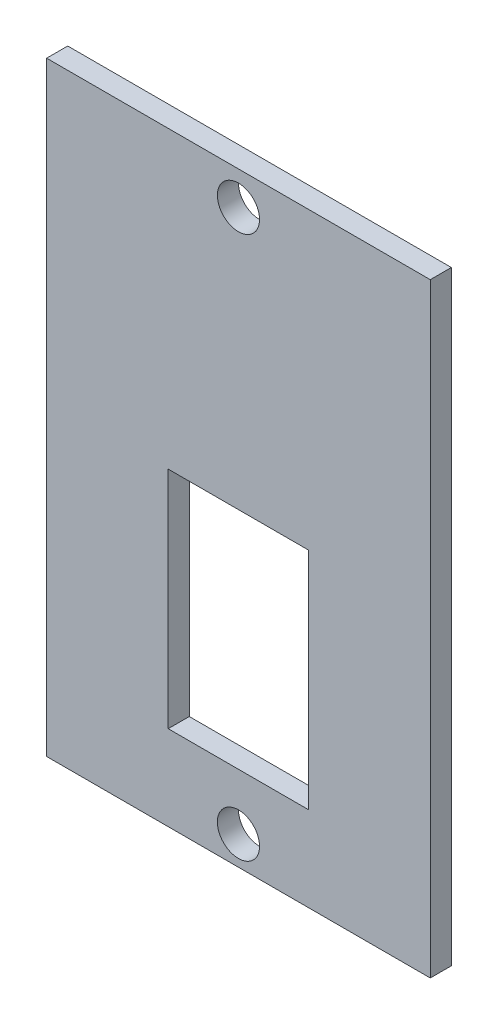
SolidWorks part; units mm, degrees
ref_plane "前视基准面" through (0, 0, 0) normal (0, 0, 1) x (1, 0, 0)
ref_plane "上视基准面" through (0, 0, 0) normal (0, 1, 0) x (1, 0, 0)
ref_plane "右视基准面" through (0, 0, 0) normal (1, 0, 0) x (0, 0, -1)
other "Configuration Table"
sketch "草图1" plane through (0, 0, 0) normal (0, 0, 1) x (1, 0, 0)
  line L0 (7.65, -10.5601) -> (-7.65, -10.5601) construction
  line L2 (-13.65, 14.6) -> (-13.65, -14.6)
  line L3 (-13.65, -14.6) -> (13.65, -14.6)
  line L4 (13.65, 14.6) -> (13.65, -14.6)
  line L5 (-13.65, 14.6) -> (13.65, -14.6) construction
  line L6 (-13.65, -14.6) -> (13.65, 14.6) construction
  line L7 (7.65, -10.5601) -> (7.65, 10.6399) construction
  line L8 (7.65, 10.6399) -> (-7.65, 10.6399) construction
  line L9 (-7.65, 10.6399) -> (-7.65, -10.5601) construction
  line L10 (0, -10.5601) -> (0, 21.7903) construction
  line L11 (5, -8.5601) -> (-5, -8.5601)
  line L12 (5, -8.5601) -> (5, 7.4399)
  line L13 (5, 7.4399) -> (-5, 7.4399)
  line L14 (-5, 7.4399) -> (-5, -8.5601)
  line L15 (-13.65, 14.6) -> (-13.65, 28.4399)
  line L16 (-13.65, 28.4399) -> (13.65, 28.4399)
  line L17 (13.65, 28.4399) -> (13.65, 14.6)
  line L18 (13.65, 14.6) -> (13.65, 28.4399)
  circle A0 centre (0, -12.5601) radius 1.5
  point P0 (0, 0)
  point P21 (0, -8.5601)
  dimension "D4" = 3
  dimension "D1" = 27.3
  dimension "D3" = 2
  dimension "D5" = 10
  dimension "D6" = 16
extrude "凸台-拉伸1" add sketch "草图1" along normal blind 1.5
sketch "草图2" plane through (0, 0, 0) normal (0, 0, -1) x (-1, 0, 0)
  circle A0 centre (0, 26.0685) radius 1.5
  point P2 (0, 26.0685)
  dimension "D1" = 3
extrude "切除-拉伸1" cut sketch "草图2" against normal blind 10
